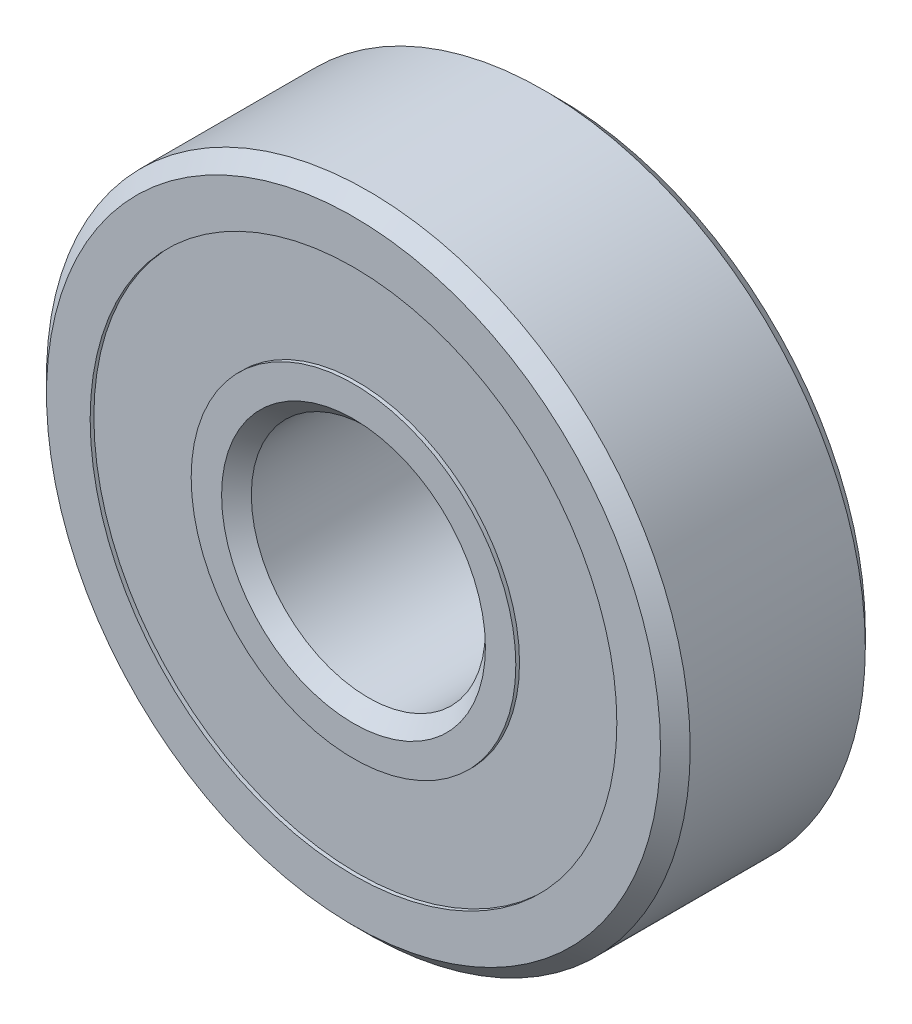
SolidWorks part; units mm, degrees
ref_plane "Front Plane" through (0, 0, 0) normal (0, 0, 1) x (1, 0, 0)
ref_plane "Top Plane" through (0, 0, 0) normal (0, 1, 0) x (1, 0, 0)
ref_plane "Right Plane" through (0, 0, 0) normal (1, 0, 0) x (0, 0, -1)
sketch "Sketch1" plane through (0, 0, 0) normal (0, 0, 1) x (1, 0, 0)
  circle A0 centre (0, 0) radius 11
  circle A1 centre (0, 0) radius 4
  dimension "D1" = 8
  dimension "D2" = 22
extrude "Boss-Extrude1" add sketch "Sketch1" along normal blind 7
chamfer "Chamfer1" distance 0.508 angle 45 3 edges at (11, 0, 0) (4, 0, 7) (11, 0, 7)
sketch "Sketch2" plane through (0, 0, 0) normal (0, 0, -1) x (-1, 0, 0)
  circle A0 centre (0, 0) radius 5.5476
  circle A1 centre (0, 0) radius 9.0001
extrude "Cut-Extrude1" cut sketch "Sketch2" against normal blind 0.127
ref_plane "Plane1" through (0, 0, 3.5) normal (0, 0, -1) x (-1, 0, 0)
mirror "Mirror1" about plane through (0, 0, 3.5) normal (0, 0, -1) of "Cut-Extrude1"
move or copy body "Body-Move/Copy1" [suppressed] bodies to move or copy 103 parameters "D1"=0, "D2"=0, "D3"=0
move or copy body "Body-Move/Copy2" [suppressed] bodies to move or copy 104 parameters "D1"=0, "D2"=0, "D3"=0
